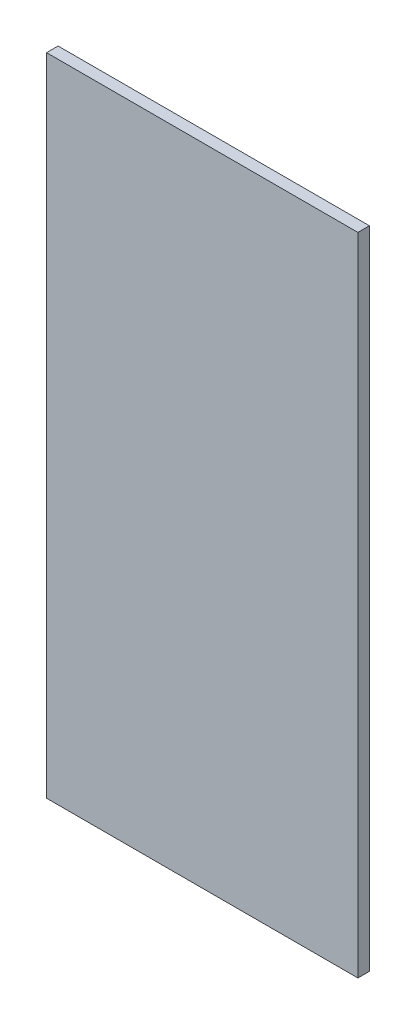
SolidWorks part; units mm, degrees
ref_plane "Front" through (0, 0, 0) normal (0, 0, 1) x (1, 0, 0)
ref_plane "Top" through (0, 0, 0) normal (0, 1, 0) x (1, 0, 0)
ref_plane "Right" through (0, 0, 0) normal (1, 0, 0) x (0, 0, -1)
sketch "Sketch1" plane through (0, 0, 0) normal (0, 0, 1) x (1, 0, 0)
  line L5 (-171.45, -355.6) -> (171.45, -355.6)
  line L6 (-171.45, -355.6) -> (-171.45, 355.6)
  line L7 (-171.45, 355.6) -> (171.45, 355.6)
  line L8 (171.45, -355.6) -> (171.45, 355.6)
  line L9 (-171.45, -355.6) -> (171.45, 355.6) construction
  line L10 (-171.45, 355.6) -> (171.45, -355.6) construction
  point P4 (0, 0)
  dimension "D1" = 342.9
  dimension "D2" = 711.2
extrude "Boss-Extrude1" add sketch "Sketch1" along normal blind 12.7
